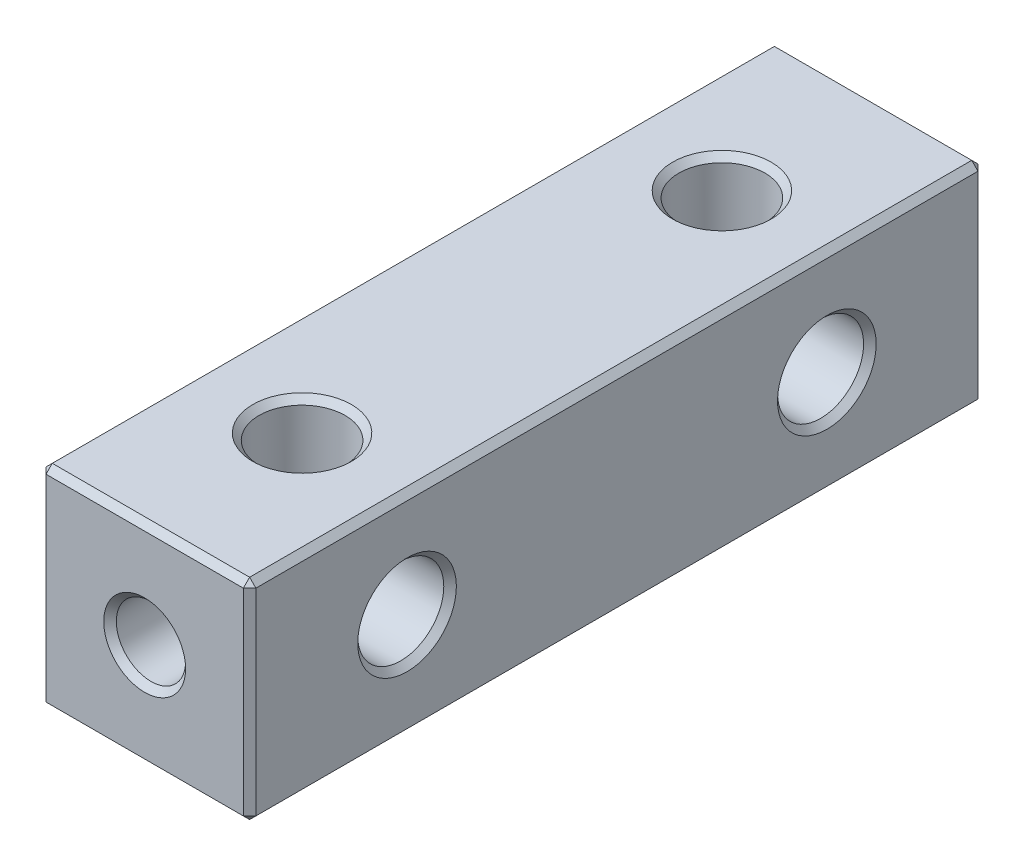
SolidWorks part; units mm, degrees
ref_plane "前视基准面" through (0, 0, 0) normal (0, 0, 1) x (1, 0, 0)
ref_plane "上视基准面" through (0, 0, 0) normal (0, 1, 0) x (1, 0, 0)
ref_plane "右视基准面" through (0, 0, 0) normal (1, 0, 0) x (0, 0, -1)
sketch "草图1" plane through (0, 0, 0) normal (0, 0, 1) x (1, 0, 0)
  line L1 (-5, 5) -> (5, 5)
  line L2 (-5, 5) -> (-5, -5)
  line L3 (-5, -5) -> (5, -5)
  line L4 (5, 5) -> (5, -5)
  line L5 (-5, 5) -> (5, -5) construction
  line L6 (-5, -5) -> (5, 5) construction
  point P0 (0, 0)
  dimension "D1" = 10
extrude "凸台-拉伸1" add sketch "草图1" along normal mid plane 35
hole_wizard "Ø4.1 (4.1) 直径孔1" positions "草图2" profile "草图3" hole size "Ø4.1" standard "GB" end condition through all
sketch "草图2" plane through (5, 0, 0) normal (1, 0, 0) x (0, 0, -1)
  line L0 (0, 0) -> (0, 50000) construction
  line L1 (-17.5, 5) -> (17.5, 5) construction
  line L2 (0, 0) -> (50000, 0) construction
  point P0 (-10, 0)
  point P2 (10, 0)
  point P10 (0, 5)
  dimension "D1" = 20
sketch "草图3" plane through (5, 0, 10) normal (0, 1, 0) x (0, 0, -1)
  line L0 (0, 0) -> (0, 10)
  line L1 (0, 10) -> (2.05, 10)
  line L2 (2.05, 10) -> (2.05, 0)
  line L5 (2.05, 0) -> (0, 0)
  line L11 (0, -6.35) -> (0, 107.95) construction
  dimension "通孔孔直径" = 4.1
  dimension "通孔孔深度" = 10
hole_wizard "Ø4.1 (4.1) 直径孔2" positions "草图4" profile "草图5" hole size "Ø4.1" standard "GB" end condition through all
sketch "草图4" plane through (0, 5, 0) normal (0, 1, 0) x (1, 0, 0)
  line L0 (0, 0) -> (0, 50000) construction
  line L1 (0, 0) -> (-50000, 0) construction
  point P0 (0, -10)
  point P2 (0, 10)
  dimension "D1" = 20
sketch "草图5" plane through (0, 5, 10) normal (1, 0, 0) x (0, 0, 1)
  line L0 (0, 0) -> (0, 10)
  line L1 (0, 10) -> (2.05, 10)
  line L2 (2.05, 10) -> (2.05, 0)
  line L5 (2.05, 0) -> (0, 0)
  line L11 (0, -6.35) -> (0, 107.95) construction
  dimension "通孔孔直径" = 4.1
  dimension "通孔孔深度" = 10
hole_wizard "M4 螺纹孔1" positions "草图6" profile "草图7" tap size "M4" standard "GB"
sketch "草图6" plane through (0, 0, 17.5) normal (0, 0, 1) x (1, 0, 0)
  point P0 (0, 0)
sketch "草图7" plane through (0, 0, 17.5) normal (1, 0, 0) x (0, -1, 0)
  line L0 (0, 0) -> (0, 5.45)
  line L1 (0, 5.45) -> (1.65, 5.45)
  line L2 (1.65, 5.45) -> (1.65, 0)
  line L5 (1.65, 0) -> (0, 0)
  line L11 (0, -6.35) -> (0, 107.95) construction
  dimension "通孔螺纹孔钻头直径" = 3.3
  dimension "通孔螺纹孔钻头深度" = 5.45
cosmetic thread "孔螺蚊线1" parameters "D2"=4
hole_wizard "M4 螺纹孔2" positions "草图8" profile "草图9" tap size "M4" standard "GB"
sketch "草图8" plane through (0, 0, -17.5) normal (0, 0, -1) x (-1, 0, 0)
  point P0 (0, 0)
sketch "草图9" plane through (0, 0, -17.5) normal (1, 0, 0) x (0, 1, 0)
  line L0 (0, 0) -> (0, 5.45)
  line L1 (0, 5.45) -> (1.65, 5.45)
  line L2 (1.65, 5.45) -> (1.65, 0)
  line L5 (1.65, 0) -> (0, 0)
  line L11 (0, -6.35) -> (0, 107.95) construction
  dimension "通孔螺纹孔钻头直径" = 3.3
  dimension "通孔螺纹孔钻头深度" = 5.45
cosmetic thread "孔螺蚊线2" parameters "D2"=4
chamfer "倒角1" distance 0.3 angle 45 22 edges at (-1.65, 0, -17.5) (1.65, 0, 17.5) (5, 0, -12.05) (5, 0, 7.95) (0, -5, -7.95) (0, -5, 12.05) (-5, 0, -12.05) (-5, 0, 7.95) (5, 0, 17.5) (5, 0, -17.5) (0, -5, 17.5) (5, -5, 0) (0, -5, -17.5) (-5, 0, 17.5) (-5, -5, 0) (-5, 0, -17.5) (5, 5, 0) (0, 5, 17.5) (-5, 5, 0) (0, 5, -17.5) (0, 5, -7.95) (0, 5, 12.05)
